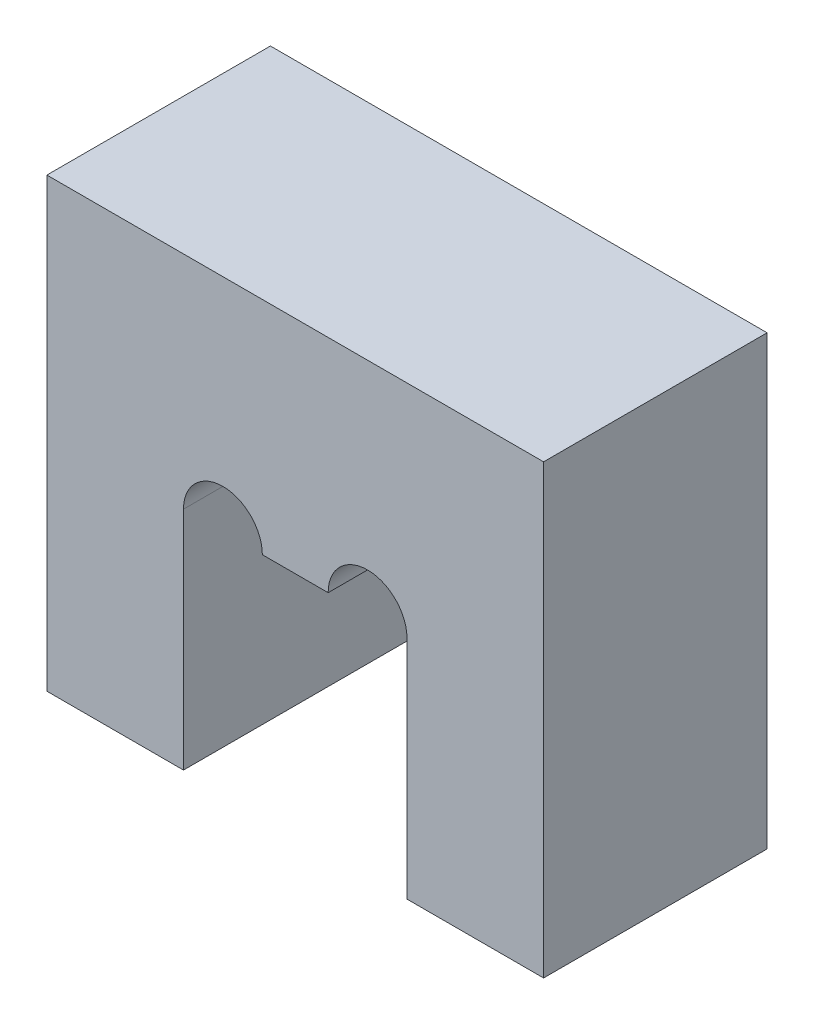
SolidWorks part; units mm, degrees
ref_plane "Piano frontale" through (0, 0, 0) normal (0, 0, 1) x (1, 0, 0)
ref_plane "Piano superiore" through (0, 0, 0) normal (0, 1, 0) x (1, 0, 0)
ref_plane "Piano destro" through (0, 0, 0) normal (1, 0, 0) x (0, 0, -1)
sketch "Schizzo1" plane through (0, 0, 0) normal (0, 0, 1) x (1, 0, 0)
  line L0 (0.4372, -19.8791) -> (11.4372, -19.8791)
  line L1 (-28.5628, 16.1209) -> (11.4372, 16.1209)
  line L2 (-28.5628, 16.1209) -> (-28.5628, -19.8791)
  line L3 (-28.5628, -19.8791) -> (-17.5628, -19.8791)
  line L4 (11.4372, 16.1209) -> (11.4372, -19.8791)
  line L5 (-11.2128, -1.6813) -> (-5.9128, -1.6813)
  line L8 (-17.5628, -1.6813) -> (-17.5628, -19.8791)
  line L10 (0.4372, -1.6813) -> (0.4372, -19.8791)
  arc A0 (0.4372, -1.6813) -> (-5.9128, -1.6813) centre (-2.7378, -1.6813) ccw
  arc A1 (-17.5628, -1.6813) -> (-11.2128, -1.6813) centre (-14.3878, -1.6813) cw
  point P0 (-8.5628, -1.8791)
  point P5 (-8.5628, -10.7802)
  dimension "D5" = 3.175
  dimension "D1" = 36
  dimension "D2" = 40
  dimension "D3" = 18
  dimension "D4" = 0
extrude "Estrusione-Estrusione1" add sketch "Schizzo1" along normal blind 18
